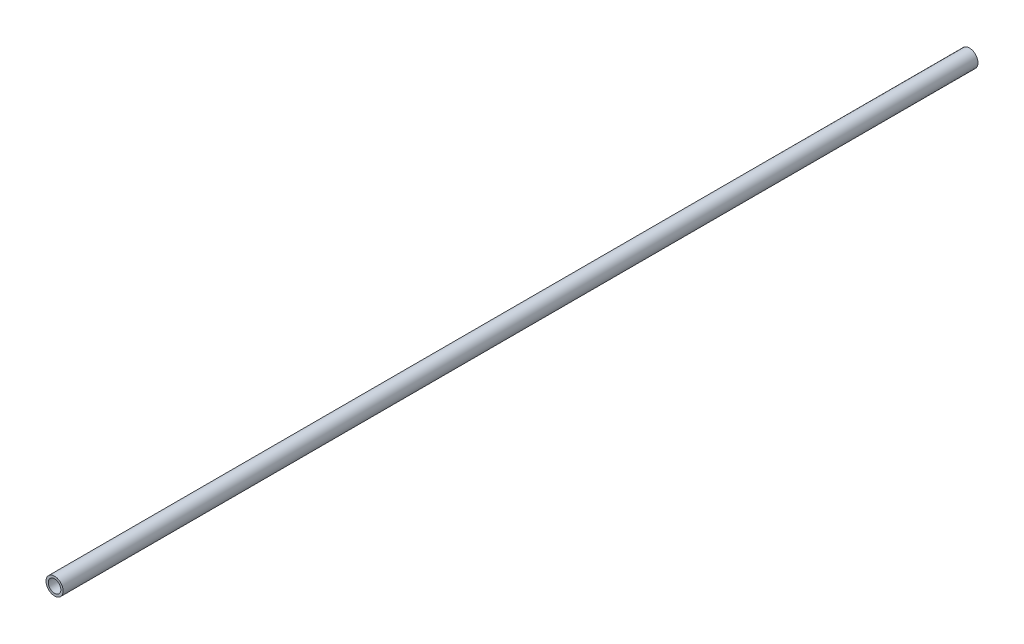
SolidWorks part; units mm, degrees
ref_plane "Front Plane" through (0, 0, 0) normal (0, 0, 1) x (1, 0, 0)
ref_plane "Top Plane" through (0, 0, 0) normal (0, 1, 0) x (1, 0, 0)
ref_plane "Right Plane" through (0, 0, 0) normal (1, 0, 0) x (0, 0, -1)
sketch "Sketch1" plane through (0, 0, 0) normal (0, 0, 1) x (1, 0, 0)
  circle A0 centre (-32.8993, 249.8477) radius 3.75
  circle A1 centre (-32.8993, 249.8477) radius 2.75
  dimension "D1" = 1
extrude "Boss-Extrude1" add sketch "Sketch1" along normal blind 400
